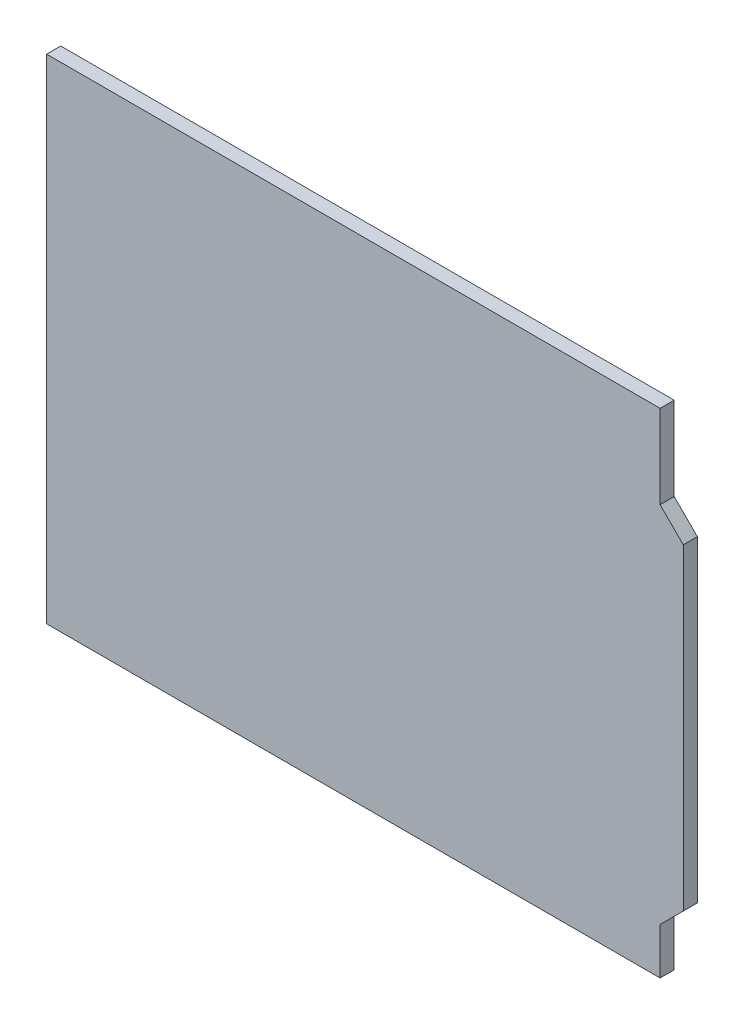
SolidWorks part; units mm, degrees
ref_plane "Alzado" through (0, 0, 0) normal (0, 0, 1) x (1, 0, 0)
ref_plane "Planta" through (0, 0, 0) normal (0, 1, 0) x (1, 0, 0)
ref_plane "Vista lateral" through (0, 0, 0) normal (1, 0, 0) x (0, 0, -1)
sketch "Croquis1" plane through (0, 0, 0) normal (0, 0, 1) x (1, 0, 0)
  line L0 (-2.5, 53.21) -> (-2.5, 44.21)
  line L1 (-2.5, 0) -> (-68.66, 0)
  line L2 (0, 7.5) -> (0, 41.71)
  line L3 (-2.5, 53.21) -> (-68.66, 53.21)
  line L4 (-68.66, 0) -> (-68.66, 53.21)
  line L5 (-2.5, 0) -> (-2.5, 5)
  line L6 (-2.5, 5) -> (0, 7.5)
  line L7 (-2.5, 44.21) -> (0, 41.71)
  dimension "D1" = 68.66
  dimension "D2" = 53.21
extrude "Saliente-Extruir1" add sketch "Croquis1" along normal blind 1.52
